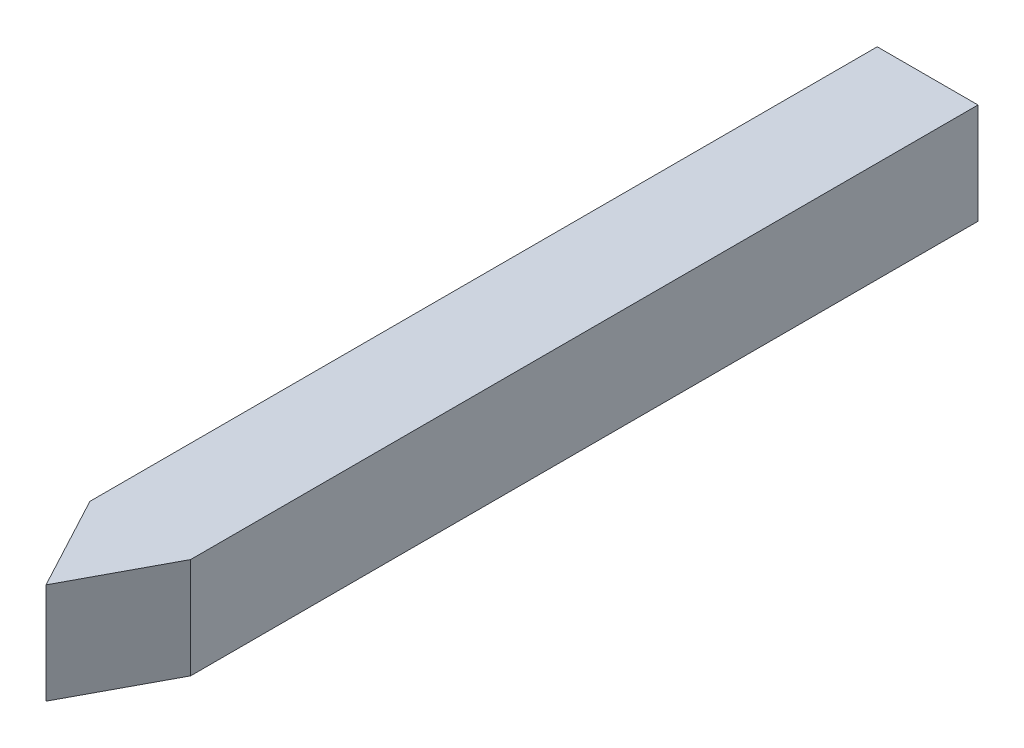
SolidWorks part; units mm, degrees
material "AISI 1020"
ref_plane "Front Plane" through (0, 0, 0) normal (0, 0, 1) x (1, 0, 0)
ref_plane "Top Plane" through (0, 0, 0) normal (0, 1, 0) x (1, 0, 0)
ref_plane "Right Plane" through (0, 0, 0) normal (1, 0, 0) x (0, 0, -1)
sketch "Sketch1" plane through (0, 0, 0) normal (0, 0, 1) x (1, 0, 0)
  line L1 (-6, -6) -> (6, -6)
  line L2 (-6, -6) -> (-6, 6)
  line L3 (-6, 6) -> (6, 6)
  line L4 (6, -6) -> (6, 6)
  line L5 (-6, -6) -> (6, 6) construction
  line L6 (-6, 6) -> (6, -6) construction
  point P0 (0, 0)
  dimension "D1" = 12
  dimension "D2" = 12
extrude "Boss-Extrude1" add sketch "Sketch1" along normal blind 105
sketch "Sketch2" plane through (0, 6, 0) normal (0, 1, 0) x (1, 0, 0)
  line L0 (0, -105) -> (-6, -93.7746)
  line L1 (6, -105) -> (-6, -105) construction
  line L2 (-6, -105) -> (-6, 0) construction
  line L3 (0, -105) -> (6, -93.7746)
  line L4 (6, -105) -> (6, 0) construction
  line L5 (6, -93.7746) -> (6, -105)
  line L6 (6, -105) -> (-6, -105)
  line L7 (-6, -105) -> (-6, -93.7746)
  line M2 (-6, 0) -> (-6, -105)
  line M3 (-6, -105) -> (6, -105)
  line M4 (6, -105) -> (6, 0)
extrude "Cut-Extrude1" cut sketch "Sketch2" against normal blind 120 contours L0 M3 M2 | L3 M3 M4
